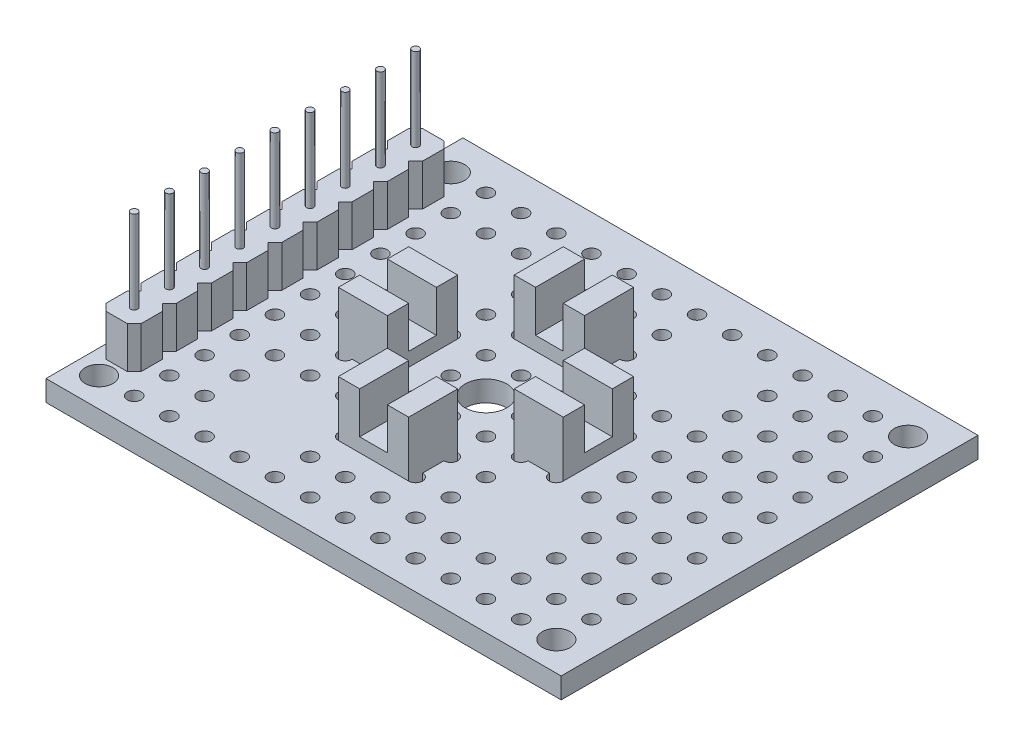
SolidWorks part; units mm, degrees
ref_plane "Спереди" through (0, 0, 0) normal (0, 0, 1) x (1, 0, 0)
ref_plane "Сверху" through (0, 0, 0) normal (0, 1, 0) x (1, 0, 0)
ref_plane "Справа" through (0, 0, 0) normal (1, 0, 0) x (0, 0, -1)
sketch "Эскиз1" plane through (0, 0, 0) normal (0, 1, 0) x (1, 0, 0)
  line L0 (1.73, 27.5) -> (34.75, 27.5) construction
  line L1 (0, 0) -> (37.2, 0)
  line L2 (0, 0) -> (0, 30.1)
  line L3 (0, 30.1) -> (37.2, 30.1)
  line L4 (37.2, 0) -> (37.2, 30.1)
  line L5 (1.73, 27.5) -> (1.73, 2.1) construction
  circle A0 centre (1.73, 27.5) radius 0.5
  circle A1 centre (4.27, 27.5) radius 0.5
  circle A2 centre (6.81, 27.5) radius 0.5
  circle A3 centre (9.35, 27.5) radius 0.5
  circle A4 centre (11.89, 27.5) radius 0.5
  circle A5 centre (14.43, 27.5) radius 0.5
  circle A6 centre (16.97, 27.5) radius 0.5
  circle A7 centre (19.51, 27.5) radius 0.5
  circle A8 centre (22.05, 27.5) radius 0.5
  circle A9 centre (24.59, 27.5) radius 0.5
  circle A10 centre (27.13, 27.5) radius 0.5
  circle A11 centre (29.67, 27.5) radius 0.5
  circle A12 centre (32.21, 27.5) radius 0.5
  circle A13 centre (34.75, 27.5) radius 0.5
  circle A14 centre (4.27, 24.96) radius 0.5
  circle A15 centre (6.81, 24.96) radius 0.5
  circle A16 centre (9.35, 24.96) radius 0.5
  circle A17 centre (11.89, 24.96) radius 0.5
  circle A18 centre (14.43, 24.96) radius 0.5
  circle A19 centre (16.97, 24.96) radius 0.5
  circle A20 centre (19.51, 24.96) radius 0.5
  circle A21 centre (22.05, 24.96) radius 0.5
  circle A22 centre (24.59, 24.96) radius 0.5
  circle A23 centre (27.13, 24.96) radius 0.5
  circle A24 centre (29.67, 24.96) radius 0.5
  circle A25 centre (32.21, 24.96) radius 0.5
  circle A26 centre (34.75, 24.96) radius 0.5
  circle A27 centre (4.27, 22.42) radius 0.5
  circle A28 centre (6.81, 22.42) radius 0.5
  circle A29 centre (9.35, 22.42) radius 0.5
  circle A30 centre (11.89, 22.42) radius 0.5
  circle A31 centre (14.43, 22.42) radius 0.5
  circle A32 centre (16.97, 22.42) radius 0.5
  circle A33 centre (19.51, 22.42) radius 0.5
  circle A34 centre (22.05, 22.42) radius 0.5
  circle A35 centre (24.59, 22.42) radius 0.5
  circle A36 centre (27.13, 22.42) radius 0.5
  circle A37 centre (29.67, 22.42) radius 0.5
  circle A38 centre (32.21, 22.42) radius 0.5
  circle A39 centre (34.75, 22.42) radius 0.5
  circle A40 centre (4.27, 19.88) radius 0.5
  circle A41 centre (6.81, 19.88) radius 0.5
  circle A42 centre (9.35, 19.88) radius 0.5
  circle A43 centre (11.89, 19.88) radius 0.5
  circle A44 centre (14.43, 19.88) radius 0.5
  circle A45 centre (16.97, 19.88) radius 0.5
  circle A46 centre (19.51, 19.88) radius 0.5
  circle A47 centre (22.05, 19.88) radius 0.5
  circle A48 centre (24.59, 19.88) radius 0.5
  circle A49 centre (27.13, 19.88) radius 0.5
  circle A50 centre (29.67, 19.88) radius 0.5
  circle A51 centre (32.21, 19.88) radius 0.5
  circle A52 centre (34.75, 19.88) radius 0.5
  circle A53 centre (4.27, 17.34) radius 0.5
  circle A54 centre (6.81, 17.34) radius 0.5
  circle A55 centre (9.35, 17.34) radius 0.5
  circle A56 centre (11.89, 17.34) radius 0.5
  circle A57 centre (14.43, 17.34) radius 0.5
  circle A58 centre (16.97, 17.34) radius 0.5
  circle A59 centre (19.51, 17.34) radius 0.5
  circle A60 centre (22.05, 17.34) radius 0.5
  circle A61 centre (24.59, 17.34) radius 0.5
  circle A62 centre (27.13, 17.34) radius 0.5
  circle A63 centre (29.67, 17.34) radius 0.5
  circle A64 centre (32.21, 17.34) radius 0.5
  circle A65 centre (34.75, 17.34) radius 0.5
  circle A66 centre (4.27, 14.8) radius 0.5
  circle A67 centre (6.81, 14.8) radius 0.5
  circle A68 centre (9.35, 14.8) radius 0.5
  circle A69 centre (11.89, 14.8) radius 0.5
  circle A70 centre (14.43, 14.8) radius 0.5
  circle A71 centre (16.97, 14.8) radius 0.5
  circle A72 centre (19.51, 14.8) radius 0.5
  circle A73 centre (22.05, 14.8) radius 0.5
  circle A74 centre (24.59, 14.8) radius 0.5
  circle A75 centre (27.13, 14.8) radius 0.5
  circle A76 centre (29.67, 14.8) radius 0.5
  circle A77 centre (32.21, 14.8) radius 0.5
  circle A78 centre (34.75, 14.8) radius 0.5
  circle A79 centre (4.27, 12.26) radius 0.5
  circle A80 centre (6.81, 12.26) radius 0.5
  circle A81 centre (9.35, 12.26) radius 0.5
  circle A82 centre (11.89, 12.26) radius 0.5
  circle A83 centre (14.43, 12.26) radius 0.5
  circle A84 centre (16.97, 12.26) radius 0.5
  circle A85 centre (19.51, 12.26) radius 0.5
  circle A86 centre (22.05, 12.26) radius 0.5
  circle A87 centre (24.59, 12.26) radius 0.5
  circle A88 centre (27.13, 12.26) radius 0.5
  circle A89 centre (29.67, 12.26) radius 0.5
  circle A90 centre (32.21, 12.26) radius 0.5
  circle A91 centre (34.75, 12.26) radius 0.5
  circle A92 centre (4.27, 9.72) radius 0.5
  circle A93 centre (6.81, 9.72) radius 0.5
  circle A94 centre (9.35, 9.72) radius 0.5
  circle A95 centre (11.89, 9.72) radius 0.5
  circle A96 centre (14.43, 9.72) radius 0.5
  circle A97 centre (16.97, 9.72) radius 0.5
  circle A98 centre (19.51, 9.72) radius 0.5
  circle A99 centre (22.05, 9.72) radius 0.5
  circle A100 centre (24.59, 9.72) radius 0.5
  circle A101 centre (27.13, 9.72) radius 0.5
  circle A102 centre (29.67, 9.72) radius 0.5
  circle A103 centre (32.21, 9.72) radius 0.5
  circle A104 centre (34.75, 9.72) radius 0.5
  circle A105 centre (4.27, 7.18) radius 0.5
  circle A106 centre (6.81, 7.18) radius 0.5
  circle A107 centre (9.35, 7.18) radius 0.5
  circle A108 centre (11.89, 7.18) radius 0.5
  circle A109 centre (14.43, 7.18) radius 0.5
  circle A110 centre (16.97, 7.18) radius 0.5
  circle A111 centre (19.51, 7.18) radius 0.5
  circle A112 centre (22.05, 7.18) radius 0.5
  circle A113 centre (24.59, 7.18) radius 0.5
  circle A114 centre (27.13, 7.18) radius 0.5
  circle A115 centre (29.67, 7.18) radius 0.5
  circle A116 centre (32.21, 7.18) radius 0.5
  circle A117 centre (34.75, 7.18) radius 0.5
  circle A118 centre (4.27, 4.64) radius 0.5
  circle A119 centre (6.81, 4.64) radius 0.5
  circle A120 centre (9.35, 4.64) radius 0.5
  circle A121 centre (11.89, 4.64) radius 0.5
  circle A122 centre (14.43, 4.64) radius 0.5
  circle A123 centre (16.97, 4.64) radius 0.5
  circle A124 centre (19.51, 4.64) radius 0.5
  circle A125 centre (22.05, 4.64) radius 0.5
  circle A126 centre (24.59, 4.64) radius 0.5
  circle A127 centre (27.13, 4.64) radius 0.5
  circle A128 centre (29.67, 4.64) radius 0.5
  circle A129 centre (32.21, 4.64) radius 0.5
  circle A130 centre (34.75, 4.64) radius 0.5
  circle A131 centre (4.27, 2.1) radius 0.5
  circle A132 centre (6.81, 2.1) radius 0.5
  circle A133 centre (9.35, 2.1) radius 0.5
  circle A134 centre (11.89, 2.1) radius 0.5
  circle A135 centre (14.43, 2.1) radius 0.5
  circle A136 centre (16.97, 2.1) radius 0.5
  circle A137 centre (19.51, 2.1) radius 0.5
  circle A138 centre (22.05, 2.1) radius 0.5
  circle A139 centre (24.59, 2.1) radius 0.5
  circle A140 centre (27.13, 2.1) radius 0.5
  circle A141 centre (29.67, 2.1) radius 0.5
  circle A142 centre (32.21, 2.1) radius 0.5
  circle A143 centre (34.75, 2.1) radius 0.5
  circle A144 centre (1.73, 24.96) radius 0.5
  circle A145 centre (1.73, 22.42) radius 0.5
  circle A146 centre (1.73, 19.88) radius 0.5
  circle A147 centre (1.73, 17.34) radius 0.5
  circle A148 centre (1.73, 14.8) radius 0.5
  circle A149 centre (1.73, 12.26) radius 0.5
  circle A150 centre (1.73, 9.72) radius 0.5
  circle A151 centre (1.73, 7.18) radius 0.5
  circle A152 centre (1.73, 4.64) radius 0.5
  circle A153 centre (1.73, 2.1) radius 0.5
  dimension "D3" = 1
  dimension "D1" = 30.1
  dimension "D2" = 37.2
  dimension "D4" = 2.6
  dimension "D5" = 1.73
  dimension "D8" = 2.54
  dimension "D9" = 2.54
  dimension "D6" = 14
  dimension "D7" = 11
extrude "Бобышка-Вытянуть1" add sketch "Эскиз1" along normal blind 1.5
sketch "Эскиз2" plane through (0, 0, 0) normal (0, -1, 0) x (1, 0, 0)
  line L1 (5.54, -22.92) -> (10.62, -22.92)
  line L2 (5.54, -22.92) -> (5.54, -19.38)
  line L3 (5.54, -19.38) -> (10.62, -19.38)
  line L4 (10.62, -22.92) -> (10.62, -19.38)
  line L5 (8.85, -3.37) -> (12.39, -3.37)
  line L6 (8.85, -3.37) -> (8.85, -8.45)
  line L7 (8.85, -8.45) -> (12.39, -8.45)
  line L8 (12.39, -3.37) -> (12.39, -8.45)
  line L9 (28.4, -10.22) -> (23.32, -10.22)
  line L10 (28.4, -10.22) -> (28.4, -6.68)
  line L11 (28.4, -6.68) -> (23.32, -6.68)
  line L12 (23.32, -10.22) -> (23.32, -6.68)
  line L13 (25.09, -26.23) -> (21.55, -26.23)
  line L14 (25.09, -26.23) -> (25.09, -21.15)
  line L15 (25.09, -21.15) -> (21.55, -21.15)
  line L16 (21.55, -26.23) -> (21.55, -21.15)
  circle A0 centre (6.81, -19.88) radius 0.5 construction
  circle A1 centre (6.81, -22.42) radius 0.5 construction
  circle A2 centre (4.27, -22.42) radius 0.5 construction
  circle A3 centre (11.89, -22.42) radius 0.5 construction
  circle A4 centre (24.59, -22.42) radius 0.5 construction
  circle A5 centre (22.05, -22.42) radius 0.5 construction
  circle A6 centre (27.13, -9.72) radius 0.5 construction
  circle A7 centre (27.13, -7.18) radius 0.5 construction
  circle A8 centre (9.35, -7.18) radius 0.5 construction
  circle A9 centre (11.89, -7.18) radius 0.5 construction
  circle A10 centre (9.35, -2.1) radius 0.5 construction
  circle A11 centre (11.89, -9.72) radius 0.5 construction
  circle A12 centre (22.05, -7.18) radius 0.5 construction
  circle A13 centre (29.67, -7.18) radius 0.5 construction
  circle A14 centre (22.05, -19.88) radius 0.5 construction
  circle A15 centre (24.59, -24.96) radius 0.5 construction
  dimension "D1" = 1.27
  dimension "D2" = 1.27
  dimension "D3" = 1.27
  dimension "D4" = 1.27
  dimension "D5" = 1.27
  dimension "D6" = 1.27
  dimension "D7" = 1.27
  dimension "D8" = 1.27
extrude "Бобышка-Вытянуть4" add sketch "Эскиз2" along normal blind 2.5 and the other way up to surface (1.5 mm away) other way up to face at (18.6, 1.5, -15.05)
fillet "Скругление1" radius 1 32 edges at (10.62, -2.5, -3.37) (12.39, -2.5, -5.91) (10.62, -2.5, -8.45) (8.85, -2.5, -5.91) (8.08, -2.5, -19.38) (10.62, -2.5, -21.15) (8.08, -2.5, -22.92) (5.54, -2.5, -21.15) (23.32, -2.5, -26.23) (21.55, -2.5, -23.69) (23.32, -2.5, -21.15) (25.09, -2.5, -23.69) (25.86, -2.5, -10.22) (23.32, -2.5, -8.45) (25.86, -2.5, -6.68) (28.4, -2.5, -8.45) (12.39, -1.25, -3.37) (8.85, -1.25, -3.37) (12.39, -1.25, -8.45) (8.85, -1.25, -8.45) (5.54, -1.25, -22.92) (5.54, -1.25, -19.38) (10.62, -1.25, -22.92) (10.62, -1.25, -19.38) (21.55, -1.25, -26.23) (21.55, -1.25, -21.15) (25.09, -1.25, -26.23) (25.09, -1.25, -21.15) (28.4, -1.25, -10.22) (23.32, -1.25, -10.22) (23.32, -1.25, -6.68) (28.4, -1.25, -6.68)
sketch "Эскиз4" plane through (0, 1.5, 0) normal (0, 1, 0) x (1, 0, 0)
  line L0 (0.46, 24.19) -> (0.96, 23.69)
  line L1 (0.96, 26.23) -> (2.5, 26.23)
  line L2 (0.46, 25.73) -> (0.46, 24.19)
  line L3 (0.96, 23.69) -> (2.5, 23.69)
  line L4 (3, 25.73) -> (3, 24.19)
  line L5 (0.46, 26.23) -> (3, 23.69) construction
  line L6 (0.46, 23.69) -> (3, 26.23) construction
  line L7 (0.46, 25.73) -> (0.96, 26.23)
  line L8 (2.5, 26.23) -> (3, 25.73)
  line L9 (3, 24.19) -> (2.5, 23.69)
  point P0 (1.73, 24.96)
  dimension "D1" = 2.54
  dimension "D2" = 2.54
extrude "Бобышка-Вытянуть5" add sketch "Эскиз4" along normal blind 3 and the other way up to surface
pattern_linear "Линейный массив1" count 9 spacing 2.54 along (0, 0, 1) of "Бобышка-Вытянуть5"
sketch "Эскиз5" plane through (0, 4.5, 0) normal (0, 1, 0) x (1, 0, 0)
  line L0 (0.71, 25.98) -> (2.75, 23.94) construction
  line L1 (0.96, 26.23) -> (0.46, 25.73) construction
  line L2 (3, 24.19) -> (2.5, 23.69) construction
  circle A0 centre (1.73, 24.96) radius 0.25
  dimension "D1" = 0.5
extrude "Бобышка-Вытянуть6" add sketch "Эскиз5" along normal blind 6
pattern_linear "Линейный массив2" count 9 spacing 2.54 along (0, 0, 1) of "Бобышка-Вытянуть6"
sketch "Эскиз6" plane through (0, 1.5, 0) normal (0, 1, 0) x (1, 0, 0)
  line L0 (19.51, 17.34) -> (14.43, 12.26) construction
  line L1 (14.43, 10.22) -> (19.51, 10.22)
  line L2 (14.43, 10.22) -> (14.43, 6.68)
  line L3 (14.43, 6.68) -> (19.51, 6.68)
  line L4 (19.51, 10.22) -> (19.51, 6.68)
  line L5 (14.43, 10.22) -> (19.51, 6.68) construction
  line L6 (14.43, 6.68) -> (19.51, 10.22) construction
  line L7 (21.55, 17.34) -> (25.09, 17.34)
  line L8 (21.55, 17.34) -> (21.55, 12.26)
  line L9 (21.55, 12.26) -> (25.09, 12.26)
  line L10 (25.09, 17.34) -> (25.09, 12.26)
  line L11 (21.55, 17.34) -> (25.09, 12.26) construction
  line L12 (21.55, 12.26) -> (25.09, 17.34) construction
  line L17 (8.85, 12.26) -> (8.85, 17.34)
  line L18 (12.39, 17.34) -> (8.85, 17.34)
  line L19 (12.39, 12.26) -> (12.39, 17.34)
  line L20 (12.39, 12.26) -> (8.85, 12.26)
  line L21 (14.43, 19.38) -> (14.43, 22.92)
  line L22 (19.51, 22.92) -> (14.43, 22.92)
  line L23 (19.51, 19.38) -> (19.51, 22.92)
  line L24 (19.51, 19.38) -> (14.43, 19.38)
  circle A2 centre (14.43, 9.72) radius 0.5 construction
  circle A3 centre (19.51, 9.72) radius 0.5 construction
  circle A4 centre (16.97, 9.72) radius 0.5 construction
  circle A5 centre (16.97, 7.18) radius 0.5 construction
  circle A6 centre (24.59, 12.26) radius 0.5 construction
  circle A7 centre (22.05, 12.26) radius 0.5 construction
  circle A8 centre (24.59, 17.34) radius 0.5 construction
  circle A9 centre (22.05, 17.34) radius 0.5 construction
  point P0 (16.97, 8.45)
  point P13 (23.32, 14.8)
  dimension "D1" = 0
  dimension "D2" = 0
  dimension "D3" = 0
extrude "Бобышка-Вытянуть7" add sketch "Эскиз6" along normal blind 4 and the other way up to surface
sketch "Эскиз7" plane through (0, 5.5, 0) normal (0, 1, 0) x (1, 0, 0)
  line L0 (14.43, 6.68) -> (19.51, 6.68) construction
  line L1 (15.97, 10.22) -> (17.97, 10.22)
  line L2 (15.97, 10.22) -> (15.97, 6.68)
  line L3 (15.97, 6.68) -> (17.97, 6.68)
  line L4 (17.97, 10.22) -> (17.97, 6.68)
  line L5 (15.97, 10.22) -> (17.97, 6.68) construction
  line L6 (15.97, 6.68) -> (17.97, 10.22) construction
  line L7 (14.43, 10.22) -> (19.51, 10.22) construction
  line L8 (19.51, 8.45) -> (14.43, 8.45) construction
  line L9 (19.51, 9.22) -> (19.51, 7.68) construction
  line L10 (14.43, 10.22) -> (14.43, 6.68) construction
  line L11 (19.51, 17.34) -> (14.43, 12.26) construction
  line L12 (23.32, 17.34) -> (23.32, 12.26) construction
  line L13 (21.55, 15.8) -> (25.09, 15.8)
  line L14 (21.55, 15.8) -> (21.55, 13.8)
  line L15 (21.55, 13.8) -> (25.09, 13.8)
  line L16 (25.09, 15.8) -> (25.09, 13.8)
  line L17 (21.55, 15.8) -> (25.09, 13.8) construction
  line L18 (21.55, 13.8) -> (25.09, 15.8) construction
  line L19 (25.09, 17.34) -> (21.55, 17.34) construction
  line L20 (21.55, 12.26) -> (25.09, 12.26) construction
  line L21 (21.55, 12.26) -> (21.55, 17.34) construction
  line L22 (8.85, 13.8) -> (8.85, 15.8)
  line L23 (12.39, 15.8) -> (8.85, 15.8)
  line L24 (12.39, 13.8) -> (12.39, 15.8)
  line L25 (12.39, 13.8) -> (8.85, 13.8)
  line L26 (15.97, 19.38) -> (15.97, 22.92)
  line L27 (17.97, 22.92) -> (15.97, 22.92)
  line L28 (17.97, 19.38) -> (17.97, 22.92)
  line L29 (17.97, 19.38) -> (15.97, 19.38)
  point P0 (16.97, 8.45)
  point P19 (23.32, 14.8)
  dimension "D1" = 2
  dimension "D2" = 2
extrude "Вырез-Вытянуть1" cut sketch "Эскиз7" against normal blind 3
sketch "Эскиз8" plane through (0, 1.5, 0) normal (0, 1, 0) x (1, 0, 0)
  circle A0 centre (1.73, 27.5) radius 1
  circle A1 centre (1.73, 2.1) radius 1
  circle A2 centre (34.75, 2.1) radius 1
  circle A3 centre (34.75, 27.5) radius 1
  dimension "D1" = 2
  dimension "D2" = 2
  dimension "D3" = 2
  dimension "D4" = 2
extrude "Вырез-Вытянуть2" cut sketch "Эскиз8" against normal through all
sketch "Эскиз9" plane through (0, 1.5, 0) normal (0, 1, 0) x (1, 0, 0)
  circle A0 centre (16.97, 14.8) radius 1.5
  dimension "D1" = 3
extrude "Вырез-Вытянуть3" cut sketch "Эскиз9" against normal through all
equation "\"D4@Эскиз1\"=(1.8+3.4)/2"
equation "\"D5@Эскиз1\"=3-2.54/2"
equation "\"D2@Эскиз2\"=\"D1@Эскиз2\""
equation "\"D3@Эскиз2\"=\"D1@Эскиз2\""
equation "\"D4@Эскиз2\"=\"D3@Эскиз2\""
equation "\"D5@Эскиз2\"=\"D3@Эскиз2\""
equation "\"D6@Эскиз2\"=\"D5@Эскиз2\""
equation "\"D7@Эскиз2\"=\"D5@Эскиз2\""
equation "\"D8@Эскиз2\"=\"D7@Эскиз2\""
equation "\"D2@Эскиз8\"=\"D1@Эскиз8\""
equation "\"D3@Эскиз8\"=\"D1@Эскиз8\""
equation "\"D4@Эскиз8\"=\"D1@Эскиз8\""
